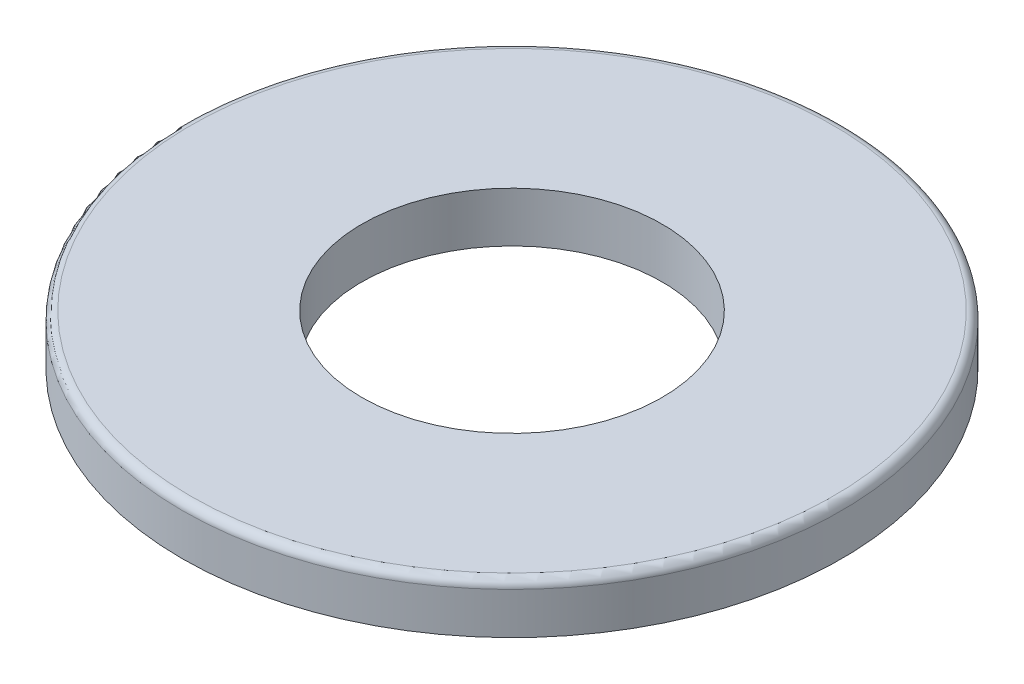
SolidWorks part; units mm, degrees
ref_plane "Front Plane" through (0, 0, 0) normal (0, 0, 1) x (1, 0, 0)
ref_plane "Top Plane" through (0, 0, 0) normal (0, 1, 0) x (1, 0, 0)
ref_plane "Right Plane" through (0, 0, 0) normal (1, 0, 0) x (0, 0, -1)
sketch "Sketch1" plane through (0, 0, 0) normal (0, 1, 0) x (1, 0, 0)
  circle A0 centre (0, 0) radius 7.9
  dimension "D1" = 15.8
extrude "Boss-Extrude1" add sketch "Sketch1" along normal blind 1.2
sketch "Sketch2" plane through (0, 1.2, 0) normal (0, 1, 0) x (1, 0, 0)
  circle A0 centre (0, 0) radius 3.6
  dimension "D1" = 7.2
extrude "Cut-Extrude1" cut sketch "Sketch2" against normal blind 1.2
fillet "Fillet1" radius 0.2 1 edges at (0, 1.2, 7.9)
